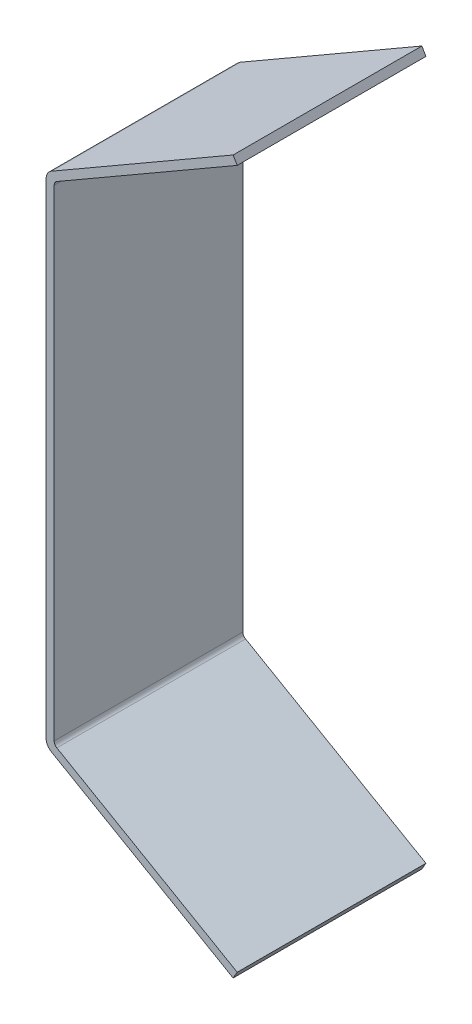
SolidWorks part; units mm, degrees
ref_plane "Alzado" through (0, 0, 0) normal (1, 0, 0) x (0, 1, 0)
ref_plane "Planta" through (0, 0, 0) normal (0, 0, 1) x (0, 1, 0)
ref_plane "Vista lateral" through (0, 0, 0) normal (0, 1, 0) x (-1, 0, 0)
sketch "Croquis1" plane through (0, 0, 0) normal (0, 0, 1) x (0, 1, 0)
  line L0 (-161.6581, 0) -> (161.6581, 0) construction
  line L1 (80.829, 140) -> (-80.829, 140) construction
  line L2 (-80.829, 140) -> (-161.6581, 0) construction
  line L3 (-161.6581, 0) -> (-80.829, -140) construction
  line L4 (-80.829, -140) -> (80.829, -140) construction
  line L5 (80.829, -140) -> (161.6581, 0) construction
  line L6 (161.6581, 0) -> (80.829, 140) construction
  line L7 (-90.39, 156.56) -> (-180.7799, 0)
  line L8 (-180.7799, 0) -> (-90.39, -156.56)
  line L9 (-90.39, -156.56) -> (90.39, -156.56)
  line L10 (90.39, -156.56) -> (180.7799, 0)
  line L11 (180.7799, 0) -> (90.39, 156.56)
  line L12 (90.39, 156.56) -> (-90.39, 156.56)
  line L13 (-92.122, 159.56) -> (-184.244, 0)
  line L14 (-184.244, 0) -> (-92.122, -159.56)
  line L15 (-92.122, -159.56) -> (92.122, -159.56)
  line L16 (92.122, -159.56) -> (184.244, 0)
  line L17 (184.244, 0) -> (92.122, 159.56)
  line L18 (92.122, 159.56) -> (-92.122, 159.56)
  line L19 (-132.183, 90.1723) -> (-129.5849, 88.6723)
  line L20 (0, 0) -> (0, 156.56) construction
  line L21 (132.183, 90.1723) -> (129.5849, 88.6723)
  circle A0 centre (0, 0) radius 140 construction
  point P1 (-138.183, 79.78)
  point P12 (0, 0)
  dimension "D1" = 280
  dimension "D4" = 12
  dimension "D2" = 16.56
  dimension "D3" = 3
extrude "Saliente-Extruir1" add sketch "Croquis1" along normal blind 70 contours L21 L17 L18 L13 L19 L7 L12 L11
fillet "Redondeo1" radius 2 2 edges at (-156.56, -90.39, 35) (-156.56, 90.39, 35)
fillet "Redondeo2" radius 4 2 edges at (-159.56, 92.122, 35) (-159.56, -92.122, 35)
